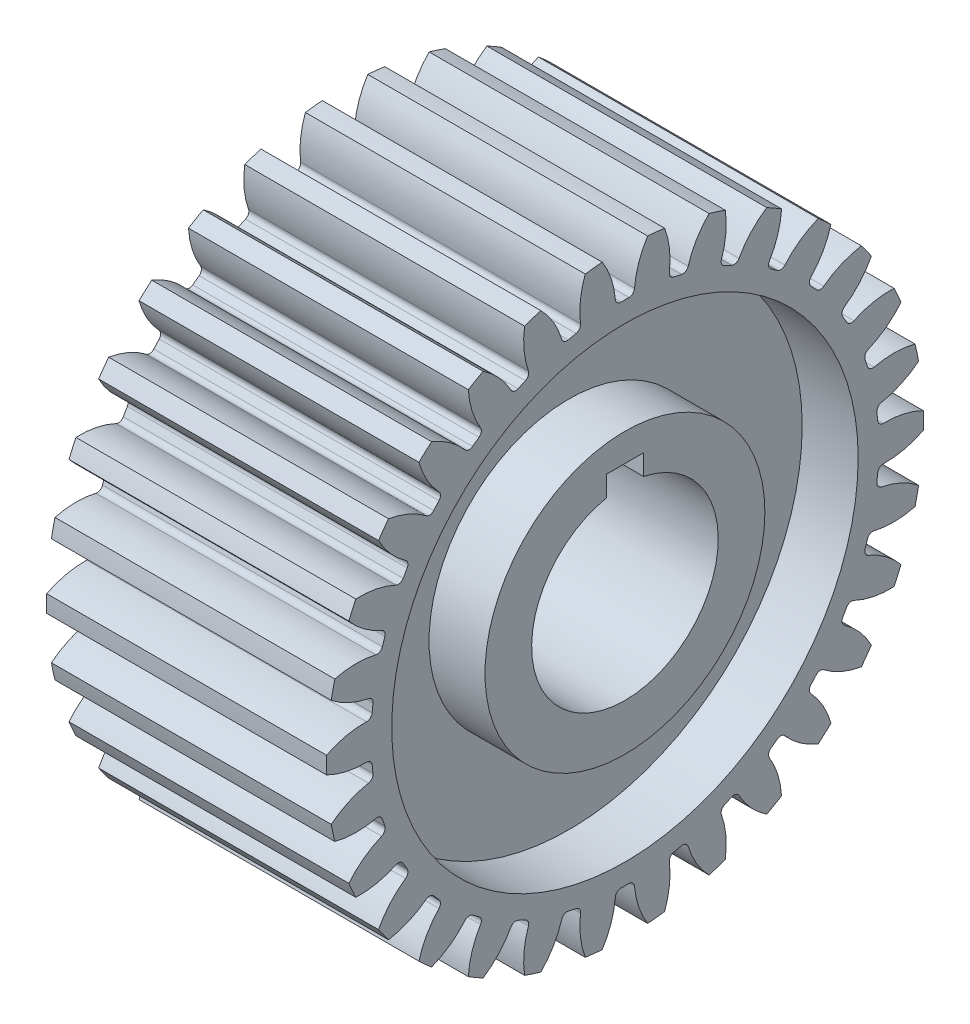
SolidWorks part; units mm, degrees
other "Camera1"
material "6063-T1"
ref_plane "Front Plane" through (0, 0, 0) normal (0, 0, 1) x (1, 0, 0)
ref_plane "Top Plane" through (0, 0, 0) normal (0, 1, 0) x (1, 0, 0)
ref_plane "Right Plane" through (0, 0, 0) normal (1, 0, 0) x (0, 0, -1)
sketch "Sketch3" plane through (0, 0, 0) normal (1, 0, 0) x (0, 0, -1)
  circle A0 centre (0, 0) radius 16
  dimension "D1" = 32
extrude "Boss-Extrude2" add sketch "Sketch3" along normal mid plane 15
sketch "Sketch4" plane through (7.5, 0, 0) normal (1, 0, 0) x (0, 0, -1)
  line L2 (-1, 4.899) -> (-1, 6)
  line L3 (-1, 6) -> (1, 6)
  line L4 (1, 4.899) -> (1, 6)
  arc A0 (-1, 4.899) -> (1, 4.899) centre (0, 0) ccw
  point P3 (0, 5)
  dimension "D1" = 10
  dimension "D2" = 2
extrude "Cut-Extrude2" cut sketch "Sketch4" against normal through all
sketch "Sketch5" plane through (7.5, 0, 0) normal (1, 0, 0) x (0, 0, -1)
  circle A0 centre (0, 0) radius 12.5
  circle A1 centre (0, 0) radius 7.5
  dimension "D1" = 25
  dimension "D2" = 15
extrude "Cut-Extrude3" cut sketch "Sketch5" against normal blind 3
mirror "Mirror1" about plane through (0, 0, 0) normal (1, 0, 0) of "Cut-Extrude3"
sketch "Sketch7" plane through (7.5, 0, 0) normal (1, 0, 0) x (0, 0, -1)
  line L0 (0, 0) -> (0, 16) construction
  line L1 (-0.2155, 13.6) -> (0.2155, 13.6)
  circle A0 centre (0, 0) radius 16 construction
  arc A1 (0.5145, 13.8752) -> (2, 16.88) centre (5.0589, 13.4981) cw
  arc A2 (-0.5145, 13.8752) -> (-2, 16.88) centre (-5.0589, 13.4981) ccw
  arc A3 (-2, 16.88) -> (2, 16.88) centre (0, -1.0085) cw
  arc A4 (0.2155, 13.6) -> (0.5145, 13.8752) centre (0.2155, 13.9) ccw
  arc A5 (-0.5145, 13.8752) -> (-0.2155, 13.6) centre (-0.2155, 13.9) ccw
  point P11 (0, 13.6)
  point P14 (0, 0)
  point P15 (0, 0)
  point P18 (0.5, 13.6)
  point P21 (-0.5, 13.6)
  dimension "D5" = 4.56
  dimension "D6" = 18
  dimension "D7" = 0.3
  dimension "D1" = 0.5
  dimension "D2" = 13.6
  dimension "D3" = 1.5
  dimension "D4" = 3.28
extrude "Cut-Extrude4" cut sketch "Sketch7" against normal through all
pattern_circular "CirPattern2" count 30 over 360 about axis through (0, 0, 0) along (1, 0, 0) of "Cut-Extrude4"
